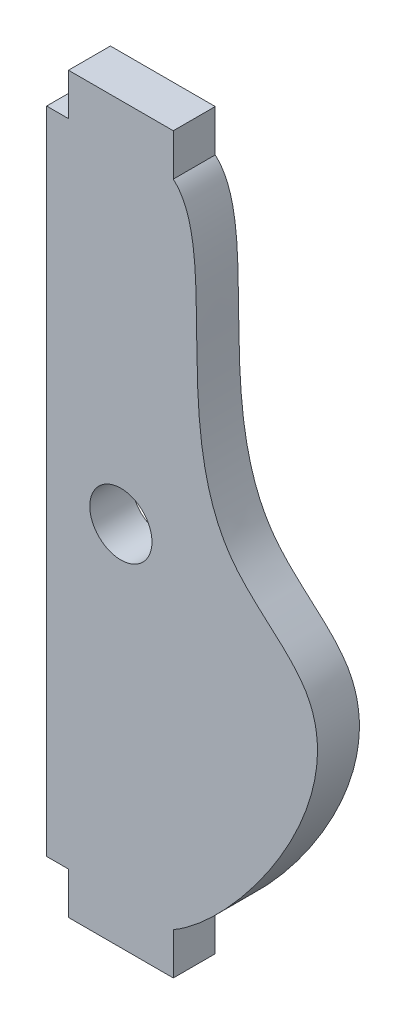
SolidWorks part; units mm, degrees
ref_plane "Alzado" through (0, 0, 0) normal (0, 0, 1) x (1, 0, 0)
ref_plane "Planta" through (0, 0, 0) normal (0, 1, 0) x (1, 0, 0)
ref_plane "Vista lateral" through (0, 0, 0) normal (1, 0, 0) x (0, 0, -1)
sketch "Croquis1" plane through (0, 0, 0) normal (0, 0, 1) x (1, 0, 0)
  line L0 (-2.5, 0) -> (-8.2747, 0) construction
  line L1 (-2.5, 15.5) -> (2.5, 15.5)
  line L2 (-2.5, 0) -> (-2.5, -15.5)
  line L3 (-2.5, -15.5) -> (2.5, -15.5)
  line L5 (-2.5, -15.5) -> (-3.5423, -15.5)
  line L6 (-3.5423, -15.5) -> (-3.5423, 15.5)
  line L7 (-2.5, 17.5) -> (2.5, 17.5)
  line L8 (-2.5, 17.5) -> (-2.5, 15.5)
  line L10 (2.5, 17.5) -> (2.5, 15.5)
  line L11 (-2.5, 17.5) -> (0, 15.5) construction
  line L12 (0, 15.5) -> (2.5, 17.5) construction
  line L13 (2.5, -17.5) -> (2.5, -15.5)
  line L14 (-2.5, -17.5) -> (2.5, -17.5)
  line L15 (-2.5, -17.5) -> (-2.5, -15.5)
  line L16 (-3.5423, 15.5) -> (-2.5, 15.5)
  circle A0 centre (0, 0) radius 1.4828
  spline S0 degree 3 poles (2.5, 15.5) (4.7784, 13.4834) (1.4031, 2.4474) (13.064, -3.9228) (5.4817, -13.8199) (2.5, -15.5) knots 0 0 0 0 0.423143 0.573503 1 1 1 1
  point P0 (0, 0)
  point P6 (0, 15.5)
  dimension "D2" = 5
  dimension "D3" = 2
  dimension "D4" = 31
extrude "Saliente-Extruir1" add sketch "Croquis1" along normal blind 2 contours S0 L1 L2 L3 A0 | L10 L7 L8 L1 | L15 L14 L13 L3
